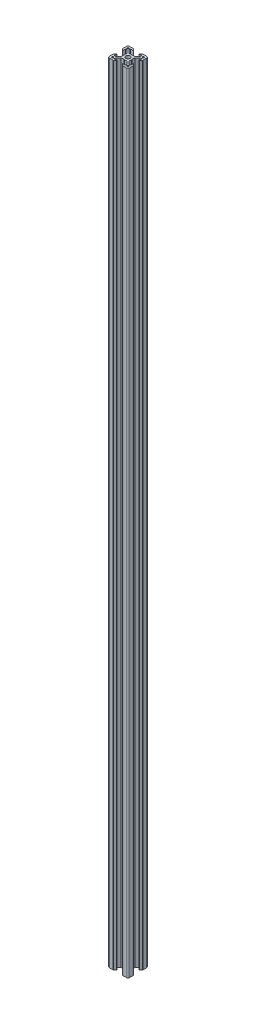
SolidWorks part; units mm, degrees
ref_plane "Front Plane" through (0, 0, 0) normal (0, 0, 1) x (1, 0, 0)
ref_plane "Top Plane" through (0, 0, 0) normal (0, 1, 0) x (1, 0, 0)
ref_plane "Right Plane" through (0, 0, 0) normal (1, 0, 0) x (0, 0, -1)
ref_plane "Plane1" through (0, 680, 0) normal (0, 1, 0) x (1, 0, 0)
sketch "Sketch1" plane through (0, 680, 0) normal (0, 1, 0) x (1, 0, 0)
  line L0 (16.2467, -17.2837) -> (16.2467, -18.911)
  line L1 (16.2467, -18.911) -> (14.6194, -18.911)
  line L2 (14.6194, -18.911) -> (14.6194, -18.3685)
  line L3 (14.6194, -18.3685) -> (15.7042, -17.2837)
  line L4 (15.7042, -17.2837) -> (16.2467, -17.2837)
  line L5 (16.2467, -4.1382) -> (15.7042, -4.1382)
  line L6 (15.7042, -4.1382) -> (14.6194, -3.0534)
  line L7 (14.6194, -3.0534) -> (14.6194, -2.511)
  line L8 (14.6194, -2.511) -> (16.2467, -2.511)
  line L9 (16.2467, -2.511) -> (16.2467, -4.1382)
  line L10 (-0.1533, -18.911) -> (-0.1533, -17.2837)
  line L11 (-0.1533, -17.2837) -> (0.3891, -17.2837)
  line L12 (0.3891, -17.2837) -> (1.4739, -18.3685)
  line L13 (1.4739, -18.3685) -> (1.4739, -18.911)
  line L14 (1.4739, -18.911) -> (-0.1533, -18.911)
  line L15 (1.4739, -2.511) -> (1.4739, -3.0534)
  line L16 (1.4739, -3.0534) -> (0.3891, -4.1382)
  line L17 (0.3891, -4.1382) -> (-0.1533, -4.1382)
  line L18 (-0.1533, -4.1382) -> (-0.1533, -2.511)
  line L19 (-0.1533, -2.511) -> (1.4739, -2.511)
  line L20 (3.2152, -0.711) -> (-0.4533, -0.711)
  line L21 (-1.9533, -2.211) -> (-1.9533, -5.811)
  line L22 (-1.7755, -6.3088) -> (-0.26, -7.8243)
  line L23 (-0.26, -7.8243) -> (-0.1533, -7.8243)
  line L24 (-0.1533, -7.8243) -> (-0.1533, -5.211)
  line L25 (-0.1533, -5.211) -> (1.486, -5.211)
  line L26 (1.486, -5.211) -> (4.1467, -7.8716)
  line L27 (4.1467, -7.8716) -> (4.1467, -10.5111)
  line L28 (4.1467, -10.5111) -> (4.3465, -10.711)
  line L29 (4.3465, -10.711) -> (4.1467, -10.9108)
  line L30 (4.1467, -10.9108) -> (4.1467, -13.5503)
  line L31 (4.1467, -13.5503) -> (1.486, -16.211)
  line L32 (1.486, -16.211) -> (-0.1533, -16.211)
  line L33 (-0.1533, -16.211) -> (-0.1533, -13.5976)
  line L34 (-0.1533, -13.5976) -> (-0.26, -13.5976)
  line L35 (-0.26, -13.5976) -> (-1.7755, -15.1132)
  line L36 (-1.9533, -15.611) -> (-1.9533, -19.211)
  line L37 (-0.4533, -20.711) -> (3.2152, -20.711)
  line L38 (3.6445, -20.5332) -> (5.16, -19.0176)
  line L39 (5.16, -19.0176) -> (5.16, -18.911)
  line L40 (5.16, -18.911) -> (2.5467, -18.911)
  line L41 (2.5467, -18.911) -> (2.5467, -17.2716)
  line L42 (2.5467, -17.2716) -> (5.2073, -14.611)
  line L43 (5.2073, -14.611) -> (7.8397, -14.611)
  line L44 (7.8397, -14.611) -> (8.0467, -14.4062)
  line L45 (8.0467, -14.4062) -> (8.2514, -14.611)
  line L46 (8.2514, -14.611) -> (10.886, -14.611)
  line L47 (10.886, -14.611) -> (13.5467, -17.2716)
  line L48 (13.5467, -17.2716) -> (13.5467, -18.911)
  line L49 (13.5467, -18.911) -> (10.9333, -18.911)
  line L50 (10.9333, -18.911) -> (10.9333, -19.0176)
  line L51 (10.9333, -19.0176) -> (12.4489, -20.5332)
  line L52 (12.8781, -20.711) -> (16.5467, -20.711)
  line L53 (18.0467, -19.211) -> (18.0467, -15.5424)
  line L54 (17.8689, -15.1132) -> (16.3533, -13.5976)
  line L55 (16.3533, -13.5976) -> (16.2467, -13.5976)
  line L56 (16.2467, -13.5976) -> (16.2467, -16.211)
  line L57 (16.2467, -16.211) -> (14.6073, -16.211)
  line L58 (14.6073, -16.211) -> (11.9467, -13.5503)
  line L59 (11.9467, -13.5503) -> (11.9467, -10.9108)
  line L60 (11.9467, -10.9108) -> (11.7468, -10.711)
  line L61 (11.7468, -10.711) -> (11.9467, -10.5111)
  line L62 (11.9467, -10.5111) -> (11.9467, -7.8716)
  line L63 (11.9467, -7.8716) -> (14.6073, -5.211)
  line L64 (14.6073, -5.211) -> (16.2467, -5.211)
  line L65 (16.2467, -5.211) -> (16.2467, -7.8243)
  line L66 (16.2467, -7.8243) -> (16.3533, -7.8243)
  line L67 (16.3533, -7.8243) -> (17.8689, -6.3088)
  line L68 (18.0467, -5.8795) -> (18.0467, -2.211)
  line L69 (16.5467, -0.711) -> (12.8781, -0.711)
  line L70 (12.4489, -0.8888) -> (10.9333, -2.4043)
  line L71 (10.9333, -2.4043) -> (10.9333, -2.511)
  line L72 (10.9333, -2.511) -> (13.5467, -2.511)
  line L73 (13.5467, -2.511) -> (13.5467, -4.1503)
  line L74 (13.5467, -4.1503) -> (10.886, -6.811)
  line L75 (10.886, -6.811) -> (8.2514, -6.811)
  line L76 (8.2514, -6.811) -> (8.0467, -7.0157)
  line L77 (8.0467, -7.0157) -> (7.8419, -6.811)
  line L78 (7.8419, -6.811) -> (5.2073, -6.811)
  line L79 (5.2073, -6.811) -> (2.5467, -4.1503)
  line L80 (2.5467, -4.1503) -> (2.5467, -2.511)
  line L81 (2.5467, -2.511) -> (5.16, -2.511)
  line L82 (5.16, -2.511) -> (5.16, -2.4043)
  line L83 (5.16, -2.4043) -> (3.6445, -0.8888)
  circle A0 centre (8.0467, -10.711) radius 2.1
  arc A1 (-0.4533, -0.711) -> (-1.9533, -2.211) centre (-0.4533, -2.211) ccw
  arc A2 (-1.9533, -5.811) -> (-1.7755, -6.3088) centre (-1.3389, -5.8722) ccw
  arc A3 (-1.7755, -15.1132) -> (-1.9533, -15.611) centre (-1.1676, -15.611) ccw
  arc A4 (-1.9533, -19.211) -> (-0.4533, -20.711) centre (-0.4533, -19.211) ccw
  arc A5 (3.2152, -20.711) -> (3.6445, -20.5332) centre (3.2152, -20.1039) ccw
  arc A6 (12.4489, -20.5332) -> (12.8781, -20.711) centre (12.8781, -20.1039) ccw
  arc A7 (16.5467, -20.711) -> (18.0467, -19.211) centre (16.5467, -19.211) ccw
  arc A8 (18.0467, -15.5424) -> (17.8689, -15.1132) centre (17.4396, -15.5424) ccw
  arc A9 (17.8689, -6.3088) -> (18.0467, -5.8795) centre (17.4396, -5.8795) ccw
  arc A10 (18.0467, -2.211) -> (16.5467, -0.711) centre (16.5467, -2.211) ccw
  arc A11 (12.8781, -0.711) -> (12.4489, -0.8888) centre (12.8781, -1.318) ccw
  arc A12 (3.6445, -0.8888) -> (3.2152, -0.711) centre (3.2152, -1.318) ccw
sketch "Sketch2" plane through (0, 680, 0) normal (0, 1, 0) x (1, 0, 0)
  line L5 (15.7042, -4.1382) -> (16.2467, -4.1382)
  line L6 (14.6194, -3.0534) -> (15.7042, -4.1382)
  line L7 (14.6194, -2.511) -> (14.6194, -3.0534)
  line L8 (16.2467, -2.511) -> (14.6194, -2.511)
  line L9 (16.2467, -4.1382) -> (16.2467, -2.511)
  line L10 (15.7042, -4.1382) -> (16.2467, -4.1382)
  line L11 (14.6194, -3.0534) -> (15.7042, -4.1382)
  line L12 (14.6194, -2.511) -> (14.6194, -3.0534)
  line L13 (16.2467, -2.511) -> (14.6194, -2.511)
  line L14 (16.2467, -4.1382) -> (16.2467, -2.511)
  line L15 (16.2467, -18.911) -> (16.2467, -17.2837)
  line L16 (14.6194, -18.911) -> (16.2467, -18.911)
  line L17 (14.6194, -18.3685) -> (14.6194, -18.911)
  line L18 (15.7042, -17.2837) -> (14.6194, -18.3685)
  line L19 (16.2467, -17.2837) -> (15.7042, -17.2837)
  line L20 (16.2467, -18.911) -> (16.2467, -17.2837)
  line L21 (14.6194, -18.911) -> (16.2467, -18.911)
  line L22 (14.6194, -18.3685) -> (14.6194, -18.911)
  line L23 (15.7042, -17.2837) -> (14.6194, -18.3685)
  line L24 (16.2467, -17.2837) -> (15.7042, -17.2837)
  line L25 (1.4739, -3.0534) -> (1.4739, -2.511)
  line L26 (0.3891, -4.1382) -> (1.4739, -3.0534)
  line L27 (-0.1533, -4.1382) -> (0.3891, -4.1382)
  line L28 (-0.1533, -2.511) -> (-0.1533, -4.1382)
  line L29 (1.4739, -2.511) -> (-0.1533, -2.511)
  line L30 (1.4739, -3.0534) -> (1.4739, -2.511)
  line L31 (0.3891, -4.1382) -> (1.4739, -3.0534)
  line L32 (-0.1533, -4.1382) -> (0.3891, -4.1382)
  line L33 (-0.1533, -2.511) -> (-0.1533, -4.1382)
  line L34 (1.4739, -2.511) -> (-0.1533, -2.511)
  line L35 (1.4739, -18.911) -> (1.4739, -18.3685)
  line L36 (1.4739, -18.3685) -> (0.3891, -17.2837)
  line L37 (0.3891, -17.2837) -> (-0.1533, -17.2837)
  line L38 (-0.1533, -17.2837) -> (-0.1533, -18.911)
  line L39 (-0.1533, -18.911) -> (1.4739, -18.911)
  line L40 (1.4739, -18.911) -> (1.4739, -18.3685)
  line L41 (1.4739, -18.3685) -> (0.3891, -17.2837)
  line L42 (0.3891, -17.2837) -> (-0.1533, -17.2837)
  line L43 (-0.1533, -17.2837) -> (-0.1533, -18.911)
  line L44 (-0.1533, -18.911) -> (1.4739, -18.911)
  line L104 (10.9333, -2.511) -> (13.5467, -2.511)
  line L105 (13.5467, -2.511) -> (13.5467, -4.1503)
  line L106 (13.5467, -4.1503) -> (10.886, -6.811)
  line L107 (10.886, -6.811) -> (8.2514, -6.811)
  line L108 (8.2514, -6.811) -> (8.0467, -7.0157)
  line L109 (8.0467, -7.0157) -> (7.8419, -6.811)
  line L110 (7.8419, -6.811) -> (5.2073, -6.811)
  line L111 (5.2073, -6.811) -> (2.5467, -4.1503)
  line L112 (2.5467, -4.1503) -> (2.5467, -2.511)
  line L113 (2.5467, -2.511) -> (5.16, -2.511)
  line L114 (5.16, -2.511) -> (5.16, -2.4043)
  line L115 (5.16, -2.4043) -> (3.6445, -0.8888)
  line L116 (3.2152, -0.711) -> (-0.4533, -0.711)
  line L117 (-1.9533, -2.211) -> (-1.9533, -5.811)
  line L118 (-1.7755, -6.3088) -> (-0.26, -7.8243)
  line L119 (-0.26, -7.8243) -> (-0.1533, -7.8243)
  line L120 (-0.1533, -7.8243) -> (-0.1533, -5.211)
  line L121 (-0.1533, -5.211) -> (1.486, -5.211)
  line L122 (1.486, -5.211) -> (4.1467, -7.8716)
  line L123 (4.1467, -7.8716) -> (4.1467, -10.5111)
  line L124 (4.1467, -10.5111) -> (4.3465, -10.711)
  line L125 (4.3465, -10.711) -> (4.1467, -10.9108)
  line L126 (4.1467, -10.9108) -> (4.1467, -13.5503)
  line L127 (4.1467, -13.5503) -> (1.486, -16.211)
  line L128 (1.486, -16.211) -> (-0.1533, -16.211)
  line L129 (-0.1533, -16.211) -> (-0.1533, -13.5976)
  line L130 (-0.1533, -13.5976) -> (-0.26, -13.5976)
  line L131 (-0.26, -13.5976) -> (-1.7755, -15.1132)
  line L132 (-1.9533, -15.611) -> (-1.9533, -19.211)
  line L133 (-0.4533, -20.711) -> (3.2152, -20.711)
  line L134 (3.6445, -20.5332) -> (5.16, -19.0176)
  line L135 (5.16, -19.0176) -> (5.16, -18.911)
  line L136 (5.16, -18.911) -> (2.5467, -18.911)
  line L137 (2.5467, -18.911) -> (2.5467, -17.2716)
  line L138 (2.5467, -17.2716) -> (5.2073, -14.611)
  line L139 (5.2073, -14.611) -> (7.8397, -14.611)
  line L140 (7.8397, -14.611) -> (8.0467, -14.4062)
  line L141 (8.0467, -14.4062) -> (8.2514, -14.611)
  line L142 (8.2514, -14.611) -> (10.886, -14.611)
  line L143 (10.886, -14.611) -> (13.5467, -17.2716)
  line L144 (13.5467, -17.2716) -> (13.5467, -18.911)
  line L145 (13.5467, -18.911) -> (10.9333, -18.911)
  line L146 (10.9333, -18.911) -> (10.9333, -19.0176)
  line L147 (10.9333, -19.0176) -> (12.4489, -20.5332)
  line L148 (12.8781, -20.711) -> (16.5467, -20.711)
  line L149 (18.0467, -19.211) -> (18.0467, -15.5424)
  line L150 (17.8689, -15.1132) -> (16.3533, -13.5976)
  line L151 (16.3533, -13.5976) -> (16.2467, -13.5976)
  line L152 (16.2467, -13.5976) -> (16.2467, -16.211)
  line L153 (16.2467, -16.211) -> (14.6073, -16.211)
  line L154 (14.6073, -16.211) -> (11.9467, -13.5503)
  line L155 (11.9467, -13.5503) -> (11.9467, -10.9108)
  line L156 (11.9467, -10.9108) -> (11.7468, -10.711)
  line L157 (11.7468, -10.711) -> (11.9467, -10.5111)
  line L158 (11.9467, -10.5111) -> (11.9467, -7.8716)
  line L159 (11.9467, -7.8716) -> (14.6073, -5.211)
  line L160 (14.6073, -5.211) -> (16.2467, -5.211)
  line L161 (16.2467, -5.211) -> (16.2467, -7.8243)
  line L162 (16.2467, -7.8243) -> (16.3533, -7.8243)
  line L163 (16.3533, -7.8243) -> (17.8689, -6.3088)
  line L164 (18.0467, -5.8795) -> (18.0467, -2.211)
  line L165 (16.5467, -0.711) -> (12.8781, -0.711)
  line L166 (12.4489, -0.8888) -> (10.9333, -2.4043)
  line L167 (10.9333, -2.4043) -> (10.9333, -2.511)
  line L168 (10.9333, -2.511) -> (13.5467, -2.511)
  line L169 (13.5467, -2.511) -> (13.5467, -4.1503)
  line L170 (13.5467, -4.1503) -> (10.886, -6.811)
  line L171 (10.886, -6.811) -> (8.2514, -6.811)
  line L172 (8.2514, -6.811) -> (8.0467, -7.0157)
  line L173 (8.0467, -7.0157) -> (7.8419, -6.811)
  line L174 (7.8419, -6.811) -> (5.2073, -6.811)
  line L175 (5.2073, -6.811) -> (2.5467, -4.1503)
  line L176 (2.5467, -4.1503) -> (2.5467, -2.511)
  line L177 (2.5467, -2.511) -> (5.16, -2.511)
  line L178 (5.16, -2.511) -> (5.16, -2.4043)
  line L179 (5.16, -2.4043) -> (3.6445, -0.8888)
  line L180 (3.2152, -0.711) -> (-0.4533, -0.711)
  line L181 (-1.9533, -2.211) -> (-1.9533, -5.811)
  line L182 (-1.7755, -6.3088) -> (-0.26, -7.8243)
  line L183 (-0.26, -7.8243) -> (-0.1533, -7.8243)
  line L184 (-0.1533, -7.8243) -> (-0.1533, -5.211)
  line L185 (-0.1533, -5.211) -> (1.486, -5.211)
  line L186 (1.486, -5.211) -> (4.1467, -7.8716)
  line L187 (4.1467, -7.8716) -> (4.1467, -10.5111)
  line L188 (4.1467, -10.5111) -> (4.3465, -10.711)
  line L189 (4.3465, -10.711) -> (4.1467, -10.9108)
  line L190 (4.1467, -10.9108) -> (4.1467, -13.5503)
  line L191 (4.1467, -13.5503) -> (1.486, -16.211)
  line L192 (1.486, -16.211) -> (-0.1533, -16.211)
  line L193 (-0.1533, -16.211) -> (-0.1533, -13.5976)
  line L194 (-0.1533, -13.5976) -> (-0.26, -13.5976)
  line L195 (-0.26, -13.5976) -> (-1.7755, -15.1132)
  line L196 (-1.9533, -15.611) -> (-1.9533, -19.211)
  line L197 (-0.4533, -20.711) -> (3.2152, -20.711)
  line L198 (3.6445, -20.5332) -> (5.16, -19.0176)
  line L199 (5.16, -19.0176) -> (5.16, -18.911)
  line L200 (5.16, -18.911) -> (2.5467, -18.911)
  line L201 (2.5467, -18.911) -> (2.5467, -17.2716)
  line L202 (2.5467, -17.2716) -> (5.2073, -14.611)
  line L203 (5.2073, -14.611) -> (7.8397, -14.611)
  line L204 (7.8397, -14.611) -> (8.0467, -14.4062)
  line L205 (8.0467, -14.4062) -> (8.2514, -14.611)
  line L206 (8.2514, -14.611) -> (10.886, -14.611)
  line L207 (10.886, -14.611) -> (13.5467, -17.2716)
  line L208 (13.5467, -17.2716) -> (13.5467, -18.911)
  line L209 (13.5467, -18.911) -> (10.9333, -18.911)
  line L210 (10.9333, -18.911) -> (10.9333, -19.0176)
  line L211 (10.9333, -19.0176) -> (12.4489, -20.5332)
  line L212 (12.8781, -20.711) -> (16.5467, -20.711)
  line L213 (18.0467, -19.211) -> (18.0467, -15.5424)
  line L214 (17.8689, -15.1132) -> (16.3533, -13.5976)
  line L215 (16.3533, -13.5976) -> (16.2467, -13.5976)
  line L216 (16.2467, -13.5976) -> (16.2467, -16.211)
  line L217 (16.2467, -16.211) -> (14.6073, -16.211)
  line L218 (14.6073, -16.211) -> (11.9467, -13.5503)
  line L219 (11.9467, -13.5503) -> (11.9467, -10.9108)
  line L220 (11.9467, -10.9108) -> (11.7468, -10.711)
  line L221 (11.7468, -10.711) -> (11.9467, -10.5111)
  line L222 (11.9467, -10.5111) -> (11.9467, -7.8716)
  line L223 (11.9467, -7.8716) -> (14.6073, -5.211)
  line L224 (14.6073, -5.211) -> (16.2467, -5.211)
  line L225 (16.2467, -5.211) -> (16.2467, -7.8243)
  line L226 (16.2467, -7.8243) -> (16.3533, -7.8243)
  line L227 (16.3533, -7.8243) -> (17.8689, -6.3088)
  line L228 (18.0467, -5.8795) -> (18.0467, -2.211)
  line L229 (16.5467, -0.711) -> (12.8781, -0.711)
  line L230 (12.4489, -0.8888) -> (10.9333, -2.4043)
  line L231 (10.9333, -2.4043) -> (10.9333, -2.511)
  circle A1 centre (8.0467, -10.711) radius 2.1
  circle A2 centre (8.0467, -10.711) radius 2.1
  arc A14 (3.6445, -0.8888) -> (3.2152, -0.711) centre (3.2152, -1.318) ccw
  arc A15 (-0.4533, -0.711) -> (-1.9533, -2.211) centre (-0.4533, -2.211) ccw
  arc A16 (-1.9533, -5.811) -> (-1.7755, -6.3088) centre (-1.3389, -5.8722) ccw
  arc A17 (-1.7755, -15.1132) -> (-1.9533, -15.611) centre (-1.1676, -15.611) ccw
  arc A18 (-1.9533, -19.211) -> (-0.4533, -20.711) centre (-0.4533, -19.211) ccw
  arc A19 (3.2152, -20.711) -> (3.6445, -20.5332) centre (3.2152, -20.1039) ccw
  arc A20 (12.4489, -20.5332) -> (12.8781, -20.711) centre (12.8781, -20.1039) ccw
  arc A21 (16.5467, -20.711) -> (18.0467, -19.211) centre (16.5467, -19.211) ccw
  arc A22 (18.0467, -15.5424) -> (17.8689, -15.1132) centre (17.4396, -15.5424) ccw
  arc A23 (17.8689, -6.3088) -> (18.0467, -5.8795) centre (17.4396, -5.8795) ccw
  arc A24 (18.0467, -2.211) -> (16.5467, -0.711) centre (16.5467, -2.211) ccw
  arc A25 (12.8781, -0.711) -> (12.4489, -0.8888) centre (12.8781, -1.318) ccw
  arc A26 (3.6445, -0.8888) -> (3.2152, -0.711) centre (3.2152, -1.318) ccw
  arc A27 (-0.4533, -0.711) -> (-1.9533, -2.211) centre (-0.4533, -2.211) ccw
  arc A28 (-1.9533, -5.811) -> (-1.7755, -6.3088) centre (-1.3389, -5.8722) ccw
  arc A29 (-1.7755, -15.1132) -> (-1.9533, -15.611) centre (-1.1676, -15.611) ccw
  arc A30 (-1.9533, -19.211) -> (-0.4533, -20.711) centre (-0.4533, -19.211) ccw
  arc A31 (3.2152, -20.711) -> (3.6445, -20.5332) centre (3.2152, -20.1039) ccw
  arc A32 (12.4489, -20.5332) -> (12.8781, -20.711) centre (12.8781, -20.1039) ccw
  arc A33 (16.5467, -20.711) -> (18.0467, -19.211) centre (16.5467, -19.211) ccw
  arc A34 (18.0467, -15.5424) -> (17.8689, -15.1132) centre (17.4396, -15.5424) ccw
  arc A35 (17.8689, -6.3088) -> (18.0467, -5.8795) centre (17.4396, -5.8795) ccw
  arc A36 (18.0467, -2.211) -> (16.5467, -0.711) centre (16.5467, -2.211) ccw
  arc A37 (12.8781, -0.711) -> (12.4489, -0.8888) centre (12.8781, -1.318) ccw
  dimension "D1" = 0
  dimension "D2" = 0
  dimension "D3" = 0
  dimension "D4" = 0
  dimension "D5" = 0
  dimension "D6" = 0
extrude "Boss-Extrude2" [suppressed] add sketch "Sketch2" against normal blind 680
sketch "Sketch3" [suppressed] plane through (0, 680, 0) normal (0, 1, 0) x (1, 0, 0)
  line L5 (15.7042, -4.1382) -> (16.2467, -4.1382)
  line L6 (14.6194, -3.0534) -> (15.7042, -4.1382)
  line L7 (14.6194, -2.511) -> (14.6194, -3.0534)
  line L8 (16.2467, -2.511) -> (14.6194, -2.511)
  line L9 (16.2467, -4.1382) -> (16.2467, -2.511)
  line L10 (15.7042, -4.1382) -> (16.2467, -4.1382)
  line L11 (14.6194, -3.0534) -> (15.7042, -4.1382)
  line L12 (14.6194, -2.511) -> (14.6194, -3.0534)
  line L13 (16.2467, -2.511) -> (14.6194, -2.511)
  line L14 (16.2467, -4.1382) -> (16.2467, -2.511)
  line L15 (16.2467, -18.911) -> (16.2467, -17.2837)
  line L16 (14.6194, -18.911) -> (16.2467, -18.911)
  line L17 (14.6194, -18.3685) -> (14.6194, -18.911)
  line L18 (15.7042, -17.2837) -> (14.6194, -18.3685)
  line L19 (16.2467, -17.2837) -> (15.7042, -17.2837)
  line L20 (16.2467, -18.911) -> (16.2467, -17.2837)
  line L21 (14.6194, -18.911) -> (16.2467, -18.911)
  line L22 (14.6194, -18.3685) -> (14.6194, -18.911)
  line L23 (15.7042, -17.2837) -> (14.6194, -18.3685)
  line L24 (16.2467, -17.2837) -> (15.7042, -17.2837)
  line L25 (1.4739, -3.0534) -> (1.4739, -2.511)
  line L26 (0.3891, -4.1382) -> (1.4739, -3.0534)
  line L27 (-0.1533, -4.1382) -> (0.3891, -4.1382)
  line L28 (-0.1533, -2.511) -> (-0.1533, -4.1382)
  line L29 (1.4739, -2.511) -> (-0.1533, -2.511)
  line L30 (1.4739, -3.0534) -> (1.4739, -2.511)
  line L31 (0.3891, -4.1382) -> (1.4739, -3.0534)
  line L32 (-0.1533, -4.1382) -> (0.3891, -4.1382)
  line L33 (-0.1533, -2.511) -> (-0.1533, -4.1382)
  line L34 (1.4739, -2.511) -> (-0.1533, -2.511)
  line L35 (1.4739, -18.911) -> (1.4739, -18.3685)
  line L36 (1.4739, -18.3685) -> (0.3891, -17.2837)
  line L37 (0.3891, -17.2837) -> (-0.1533, -17.2837)
  line L38 (-0.1533, -17.2837) -> (-0.1533, -18.911)
  line L39 (-0.1533, -18.911) -> (1.4739, -18.911)
  line L40 (1.4739, -18.911) -> (1.4739, -18.3685)
  line L41 (1.4739, -18.3685) -> (0.3891, -17.2837)
  line L42 (0.3891, -17.2837) -> (-0.1533, -17.2837)
  line L43 (-0.1533, -17.2837) -> (-0.1533, -18.911)
  line L44 (-0.1533, -18.911) -> (1.4739, -18.911)
  line L104 (10.9333, -2.511) -> (13.5467, -2.511)
  line L105 (13.5467, -2.511) -> (13.5467, -4.1503)
  line L106 (13.5467, -4.1503) -> (10.886, -6.811)
  line L107 (10.886, -6.811) -> (8.2514, -6.811)
  line L108 (8.2514, -6.811) -> (8.0467, -7.0157)
  line L109 (8.0467, -7.0157) -> (7.8419, -6.811)
  line L110 (7.8419, -6.811) -> (5.2073, -6.811)
  line L111 (5.2073, -6.811) -> (2.5467, -4.1503)
  line L112 (2.5467, -4.1503) -> (2.5467, -2.511)
  line L113 (2.5467, -2.511) -> (5.16, -2.511)
  line L114 (5.16, -2.511) -> (5.16, -2.4043)
  line L115 (5.16, -2.4043) -> (3.6445, -0.8888)
  line L116 (3.2152, -0.711) -> (-0.4533, -0.711)
  line L117 (-1.9533, -2.211) -> (-1.9533, -5.811)
  line L118 (-1.7755, -6.3088) -> (-0.26, -7.8243)
  line L119 (-0.26, -7.8243) -> (-0.1533, -7.8243)
  line L120 (-0.1533, -7.8243) -> (-0.1533, -5.211)
  line L121 (-0.1533, -5.211) -> (1.486, -5.211)
  line L122 (1.486, -5.211) -> (4.1467, -7.8716)
  line L123 (4.1467, -7.8716) -> (4.1467, -10.5111)
  line L124 (4.1467, -10.5111) -> (4.3465, -10.711)
  line L125 (4.3465, -10.711) -> (4.1467, -10.9108)
  line L126 (4.1467, -10.9108) -> (4.1467, -13.5503)
  line L127 (4.1467, -13.5503) -> (1.486, -16.211)
  line L128 (1.486, -16.211) -> (-0.1533, -16.211)
  line L129 (-0.1533, -16.211) -> (-0.1533, -13.5976)
  line L130 (-0.1533, -13.5976) -> (-0.26, -13.5976)
  line L131 (-0.26, -13.5976) -> (-1.7755, -15.1132)
  line L132 (-1.9533, -15.611) -> (-1.9533, -19.211)
  line L133 (-0.4533, -20.711) -> (3.2152, -20.711)
  line L134 (3.6445, -20.5332) -> (5.16, -19.0176)
  line L135 (5.16, -19.0176) -> (5.16, -18.911)
  line L136 (5.16, -18.911) -> (2.5467, -18.911)
  line L137 (2.5467, -18.911) -> (2.5467, -17.2716)
  line L138 (2.5467, -17.2716) -> (5.2073, -14.611)
  line L139 (5.2073, -14.611) -> (7.8397, -14.611)
  line L140 (7.8397, -14.611) -> (8.0467, -14.4062)
  line L141 (8.0467, -14.4062) -> (8.2514, -14.611)
  line L142 (8.2514, -14.611) -> (10.886, -14.611)
  line L143 (10.886, -14.611) -> (13.5467, -17.2716)
  line L144 (13.5467, -17.2716) -> (13.5467, -18.911)
  line L145 (13.5467, -18.911) -> (10.9333, -18.911)
  line L146 (10.9333, -18.911) -> (10.9333, -19.0176)
  line L147 (10.9333, -19.0176) -> (12.4489, -20.5332)
  line L148 (12.8781, -20.711) -> (16.5467, -20.711)
  line L149 (18.0467, -19.211) -> (18.0467, -15.5424)
  line L150 (17.8689, -15.1132) -> (16.3533, -13.5976)
  line L151 (16.3533, -13.5976) -> (16.2467, -13.5976)
  line L152 (16.2467, -13.5976) -> (16.2467, -16.211)
  line L153 (16.2467, -16.211) -> (14.6073, -16.211)
  line L154 (14.6073, -16.211) -> (11.9467, -13.5503)
  line L155 (11.9467, -13.5503) -> (11.9467, -10.9108)
  line L156 (11.9467, -10.9108) -> (11.7468, -10.711)
  line L157 (11.7468, -10.711) -> (11.9467, -10.5111)
  line L158 (11.9467, -10.5111) -> (11.9467, -7.8716)
  line L159 (11.9467, -7.8716) -> (14.6073, -5.211)
  line L160 (14.6073, -5.211) -> (16.2467, -5.211)
  line L161 (16.2467, -5.211) -> (16.2467, -7.8243)
  line L162 (16.2467, -7.8243) -> (16.3533, -7.8243)
  line L163 (16.3533, -7.8243) -> (17.8689, -6.3088)
  line L164 (18.0467, -5.8795) -> (18.0467, -2.211)
  line L165 (16.5467, -0.711) -> (12.8781, -0.711)
  line L166 (12.4489, -0.8888) -> (10.9333, -2.4043)
  line L167 (10.9333, -2.4043) -> (10.9333, -2.511)
  line L168 (10.9333, -2.511) -> (13.5467, -2.511)
  line L169 (13.5467, -2.511) -> (13.5467, -4.1503)
  line L170 (13.5467, -4.1503) -> (10.886, -6.811)
  line L171 (10.886, -6.811) -> (8.2514, -6.811)
  line L172 (8.2514, -6.811) -> (8.0467, -7.0157)
  line L173 (8.0467, -7.0157) -> (7.8419, -6.811)
  line L174 (7.8419, -6.811) -> (5.2073, -6.811)
  line L175 (5.2073, -6.811) -> (2.5467, -4.1503)
  line L176 (2.5467, -4.1503) -> (2.5467, -2.511)
  line L177 (2.5467, -2.511) -> (5.16, -2.511)
  line L178 (5.16, -2.511) -> (5.16, -2.4043)
  line L179 (5.16, -2.4043) -> (3.6445, -0.8888)
  line L180 (3.2152, -0.711) -> (-0.4533, -0.711)
  line L181 (-1.9533, -2.211) -> (-1.9533, -5.811)
  line L182 (-1.7755, -6.3088) -> (-0.26, -7.8243)
  line L183 (-0.26, -7.8243) -> (-0.1533, -7.8243)
  line L184 (-0.1533, -7.8243) -> (-0.1533, -5.211)
  line L185 (-0.1533, -5.211) -> (1.486, -5.211)
  line L186 (1.486, -5.211) -> (4.1467, -7.8716)
  line L187 (4.1467, -7.8716) -> (4.1467, -10.5111)
  line L188 (4.1467, -10.5111) -> (4.3465, -10.711)
  line L189 (4.3465, -10.711) -> (4.1467, -10.9108)
  line L190 (4.1467, -10.9108) -> (4.1467, -13.5503)
  line L191 (4.1467, -13.5503) -> (1.486, -16.211)
  line L192 (1.486, -16.211) -> (-0.1533, -16.211)
  line L193 (-0.1533, -16.211) -> (-0.1533, -13.5976)
  line L194 (-0.1533, -13.5976) -> (-0.26, -13.5976)
  line L195 (-0.26, -13.5976) -> (-1.7755, -15.1132)
  line L196 (-1.9533, -15.611) -> (-1.9533, -19.211)
  line L197 (-0.4533, -20.711) -> (3.2152, -20.711)
  line L198 (3.6445, -20.5332) -> (5.16, -19.0176)
  line L199 (5.16, -19.0176) -> (5.16, -18.911)
  line L200 (5.16, -18.911) -> (2.5467, -18.911)
  line L201 (2.5467, -18.911) -> (2.5467, -17.2716)
  line L202 (2.5467, -17.2716) -> (5.2073, -14.611)
  line L203 (5.2073, -14.611) -> (7.8397, -14.611)
  line L204 (7.8397, -14.611) -> (8.0467, -14.4062)
  line L205 (8.0467, -14.4062) -> (8.2514, -14.611)
  line L206 (8.2514, -14.611) -> (10.886, -14.611)
  line L207 (10.886, -14.611) -> (13.5467, -17.2716)
  line L208 (13.5467, -17.2716) -> (13.5467, -18.911)
  line L209 (13.5467, -18.911) -> (10.9333, -18.911)
  line L210 (10.9333, -18.911) -> (10.9333, -19.0176)
  line L211 (10.9333, -19.0176) -> (12.4489, -20.5332)
  line L212 (12.8781, -20.711) -> (16.5467, -20.711)
  line L213 (18.0467, -19.211) -> (18.0467, -15.5424)
  line L214 (17.8689, -15.1132) -> (16.3533, -13.5976)
  line L215 (16.3533, -13.5976) -> (16.2467, -13.5976)
  line L216 (16.2467, -13.5976) -> (16.2467, -16.211)
  line L217 (16.2467, -16.211) -> (14.6073, -16.211)
  line L218 (14.6073, -16.211) -> (11.9467, -13.5503)
  line L219 (11.9467, -13.5503) -> (11.9467, -10.9108)
  line L220 (11.9467, -10.9108) -> (11.7468, -10.711)
  line L221 (11.7468, -10.711) -> (11.9467, -10.5111)
  line L222 (11.9467, -10.5111) -> (11.9467, -7.8716)
  line L223 (11.9467, -7.8716) -> (14.6073, -5.211)
  line L224 (14.6073, -5.211) -> (16.2467, -5.211)
  line L225 (16.2467, -5.211) -> (16.2467, -7.8243)
  line L226 (16.2467, -7.8243) -> (16.3533, -7.8243)
  line L227 (16.3533, -7.8243) -> (17.8689, -6.3088)
  line L228 (18.0467, -5.8795) -> (18.0467, -2.211)
  line L229 (16.5467, -0.711) -> (12.8781, -0.711)
  line L230 (12.4489, -0.8888) -> (10.9333, -2.4043)
  line L231 (10.9333, -2.4043) -> (10.9333, -2.511)
  circle A1 centre (8.0467, -10.711) radius 2.1
  circle A2 centre (8.0467, -10.711) radius 2.1
  arc A14 (3.6445, -0.8888) -> (3.2152, -0.711) centre (3.2152, -1.318) ccw
  arc A15 (-0.4533, -0.711) -> (-1.9533, -2.211) centre (-0.4533, -2.211) ccw
  arc A16 (-1.9533, -5.811) -> (-1.7755, -6.3088) centre (-1.3389, -5.8722) ccw
  arc A17 (-1.7755, -15.1132) -> (-1.9533, -15.611) centre (-1.1676, -15.611) ccw
  arc A18 (-1.9533, -19.211) -> (-0.4533, -20.711) centre (-0.4533, -19.211) ccw
  arc A19 (3.2152, -20.711) -> (3.6445, -20.5332) centre (3.2152, -20.1039) ccw
  arc A20 (12.4489, -20.5332) -> (12.8781, -20.711) centre (12.8781, -20.1039) ccw
  arc A21 (16.5467, -20.711) -> (18.0467, -19.211) centre (16.5467, -19.211) ccw
  arc A22 (18.0467, -15.5424) -> (17.8689, -15.1132) centre (17.4396, -15.5424) ccw
  arc A23 (17.8689, -6.3088) -> (18.0467, -5.8795) centre (17.4396, -5.8795) ccw
  arc A24 (18.0467, -2.211) -> (16.5467, -0.711) centre (16.5467, -2.211) ccw
  arc A25 (12.8781, -0.711) -> (12.4489, -0.8888) centre (12.8781, -1.318) ccw
  arc A26 (3.6445, -0.8888) -> (3.2152, -0.711) centre (3.2152, -1.318) ccw
  arc A27 (-0.4533, -0.711) -> (-1.9533, -2.211) centre (-0.4533, -2.211) ccw
  arc A28 (-1.9533, -5.811) -> (-1.7755, -6.3088) centre (-1.3389, -5.8722) ccw
  arc A29 (-1.7755, -15.1132) -> (-1.9533, -15.611) centre (-1.1676, -15.611) ccw
  arc A30 (-1.9533, -19.211) -> (-0.4533, -20.711) centre (-0.4533, -19.211) ccw
  arc A31 (3.2152, -20.711) -> (3.6445, -20.5332) centre (3.2152, -20.1039) ccw
  arc A32 (12.4489, -20.5332) -> (12.8781, -20.711) centre (12.8781, -20.1039) ccw
  arc A33 (16.5467, -20.711) -> (18.0467, -19.211) centre (16.5467, -19.211) ccw
  arc A34 (18.0467, -15.5424) -> (17.8689, -15.1132) centre (17.4396, -15.5424) ccw
  arc A35 (17.8689, -6.3088) -> (18.0467, -5.8795) centre (17.4396, -5.8795) ccw
  arc A36 (18.0467, -2.211) -> (16.5467, -0.711) centre (16.5467, -2.211) ccw
  arc A37 (12.8781, -0.711) -> (12.4489, -0.8888) centre (12.8781, -1.318) ccw
  dimension "D1" = 0
  dimension "D2" = 0
  dimension "D3" = 0
  dimension "D4" = 0
  dimension "D5" = 0
  dimension "D6" = 0
extrude "Boss-Extrude3" [suppressed] add sketch "Sketch3" against normal blind 530
sketch "Sketch5" plane through (0, 680, 0) normal (0, 1, 0) x (1, 0, 0)
  line L5 (15.7042, -4.1382) -> (16.2467, -4.1382)
  line L6 (14.6194, -3.0534) -> (15.7042, -4.1382)
  line L7 (14.6194, -2.511) -> (14.6194, -3.0534)
  line L8 (16.2467, -2.511) -> (14.6194, -2.511)
  line L9 (16.2467, -4.1382) -> (16.2467, -2.511)
  line L10 (15.7042, -4.1382) -> (16.2467, -4.1382)
  line L11 (14.6194, -3.0534) -> (15.7042, -4.1382)
  line L12 (14.6194, -2.511) -> (14.6194, -3.0534)
  line L13 (16.2467, -2.511) -> (14.6194, -2.511)
  line L14 (16.2467, -4.1382) -> (16.2467, -2.511)
  line L15 (16.2467, -18.911) -> (16.2467, -17.2837)
  line L16 (14.6194, -18.911) -> (16.2467, -18.911)
  line L17 (14.6194, -18.3685) -> (14.6194, -18.911)
  line L18 (15.7042, -17.2837) -> (14.6194, -18.3685)
  line L19 (16.2467, -17.2837) -> (15.7042, -17.2837)
  line L20 (16.2467, -18.911) -> (16.2467, -17.2837)
  line L21 (14.6194, -18.911) -> (16.2467, -18.911)
  line L22 (14.6194, -18.3685) -> (14.6194, -18.911)
  line L23 (15.7042, -17.2837) -> (14.6194, -18.3685)
  line L24 (16.2467, -17.2837) -> (15.7042, -17.2837)
  line L25 (1.4739, -3.0534) -> (1.4739, -2.511)
  line L26 (0.3891, -4.1382) -> (1.4739, -3.0534)
  line L27 (-0.1533, -4.1382) -> (0.3891, -4.1382)
  line L28 (-0.1533, -2.511) -> (-0.1533, -4.1382)
  line L29 (1.4739, -2.511) -> (-0.1533, -2.511)
  line L30 (1.4739, -3.0534) -> (1.4739, -2.511)
  line L31 (0.3891, -4.1382) -> (1.4739, -3.0534)
  line L32 (-0.1533, -4.1382) -> (0.3891, -4.1382)
  line L33 (-0.1533, -2.511) -> (-0.1533, -4.1382)
  line L34 (1.4739, -2.511) -> (-0.1533, -2.511)
  line L35 (1.4739, -18.911) -> (1.4739, -18.3685)
  line L36 (1.4739, -18.3685) -> (0.3891, -17.2837)
  line L37 (0.3891, -17.2837) -> (-0.1533, -17.2837)
  line L38 (-0.1533, -17.2837) -> (-0.1533, -18.911)
  line L39 (-0.1533, -18.911) -> (1.4739, -18.911)
  line L40 (1.4739, -18.911) -> (1.4739, -18.3685)
  line L41 (1.4739, -18.3685) -> (0.3891, -17.2837)
  line L42 (0.3891, -17.2837) -> (-0.1533, -17.2837)
  line L43 (-0.1533, -17.2837) -> (-0.1533, -18.911)
  line L44 (-0.1533, -18.911) -> (1.4739, -18.911)
  line L104 (10.9333, -2.511) -> (13.5467, -2.511)
  line L105 (13.5467, -2.511) -> (13.5467, -4.1503)
  line L106 (13.5467, -4.1503) -> (10.886, -6.811)
  line L107 (10.886, -6.811) -> (8.2514, -6.811)
  line L108 (8.2514, -6.811) -> (8.0467, -7.0157)
  line L109 (8.0467, -7.0157) -> (7.8419, -6.811)
  line L110 (7.8419, -6.811) -> (5.2073, -6.811)
  line L111 (5.2073, -6.811) -> (2.5467, -4.1503)
  line L112 (2.5467, -4.1503) -> (2.5467, -2.511)
  line L113 (2.5467, -2.511) -> (5.16, -2.511)
  line L114 (5.16, -2.511) -> (5.16, -2.4043)
  line L115 (5.16, -2.4043) -> (3.6445, -0.8888)
  line L116 (3.2152, -0.711) -> (-0.4533, -0.711)
  line L117 (-1.9533, -2.211) -> (-1.9533, -5.811)
  line L118 (-1.7755, -6.3088) -> (-0.26, -7.8243)
  line L119 (-0.26, -7.8243) -> (-0.1533, -7.8243)
  line L120 (-0.1533, -7.8243) -> (-0.1533, -5.211)
  line L121 (-0.1533, -5.211) -> (1.486, -5.211)
  line L122 (1.486, -5.211) -> (4.1467, -7.8716)
  line L123 (4.1467, -7.8716) -> (4.1467, -10.5111)
  line L124 (4.1467, -10.5111) -> (4.3465, -10.711)
  line L125 (4.3465, -10.711) -> (4.1467, -10.9108)
  line L126 (4.1467, -10.9108) -> (4.1467, -13.5503)
  line L127 (4.1467, -13.5503) -> (1.486, -16.211)
  line L128 (1.486, -16.211) -> (-0.1533, -16.211)
  line L129 (-0.1533, -16.211) -> (-0.1533, -13.5976)
  line L130 (-0.1533, -13.5976) -> (-0.26, -13.5976)
  line L131 (-0.26, -13.5976) -> (-1.7755, -15.1132)
  line L132 (-1.9533, -15.611) -> (-1.9533, -19.211)
  line L133 (-0.4533, -20.711) -> (3.2152, -20.711)
  line L134 (3.6445, -20.5332) -> (5.16, -19.0176)
  line L135 (5.16, -19.0176) -> (5.16, -18.911)
  line L136 (5.16, -18.911) -> (2.5467, -18.911)
  line L137 (2.5467, -18.911) -> (2.5467, -17.2716)
  line L138 (2.5467, -17.2716) -> (5.2073, -14.611)
  line L139 (5.2073, -14.611) -> (7.8397, -14.611)
  line L140 (7.8397, -14.611) -> (8.0467, -14.4062)
  line L141 (8.0467, -14.4062) -> (8.2514, -14.611)
  line L142 (8.2514, -14.611) -> (10.886, -14.611)
  line L143 (10.886, -14.611) -> (13.5467, -17.2716)
  line L144 (13.5467, -17.2716) -> (13.5467, -18.911)
  line L145 (13.5467, -18.911) -> (10.9333, -18.911)
  line L146 (10.9333, -18.911) -> (10.9333, -19.0176)
  line L147 (10.9333, -19.0176) -> (12.4489, -20.5332)
  line L148 (12.8781, -20.711) -> (16.5467, -20.711)
  line L149 (18.0467, -19.211) -> (18.0467, -15.5424)
  line L150 (17.8689, -15.1132) -> (16.3533, -13.5976)
  line L151 (16.3533, -13.5976) -> (16.2467, -13.5976)
  line L152 (16.2467, -13.5976) -> (16.2467, -16.211)
  line L153 (16.2467, -16.211) -> (14.6073, -16.211)
  line L154 (14.6073, -16.211) -> (11.9467, -13.5503)
  line L155 (11.9467, -13.5503) -> (11.9467, -10.9108)
  line L156 (11.9467, -10.9108) -> (11.7468, -10.711)
  line L157 (11.7468, -10.711) -> (11.9467, -10.5111)
  line L158 (11.9467, -10.5111) -> (11.9467, -7.8716)
  line L159 (11.9467, -7.8716) -> (14.6073, -5.211)
  line L160 (14.6073, -5.211) -> (16.2467, -5.211)
  line L161 (16.2467, -5.211) -> (16.2467, -7.8243)
  line L162 (16.2467, -7.8243) -> (16.3533, -7.8243)
  line L163 (16.3533, -7.8243) -> (17.8689, -6.3088)
  line L164 (18.0467, -5.8795) -> (18.0467, -2.211)
  line L165 (16.5467, -0.711) -> (12.8781, -0.711)
  line L166 (12.4489, -0.8888) -> (10.9333, -2.4043)
  line L167 (10.9333, -2.4043) -> (10.9333, -2.511)
  line L168 (10.9333, -2.511) -> (13.5467, -2.511)
  line L169 (13.5467, -2.511) -> (13.5467, -4.1503)
  line L170 (13.5467, -4.1503) -> (10.886, -6.811)
  line L171 (10.886, -6.811) -> (8.2514, -6.811)
  line L172 (8.2514, -6.811) -> (8.0467, -7.0157)
  line L173 (8.0467, -7.0157) -> (7.8419, -6.811)
  line L174 (7.8419, -6.811) -> (5.2073, -6.811)
  line L175 (5.2073, -6.811) -> (2.5467, -4.1503)
  line L176 (2.5467, -4.1503) -> (2.5467, -2.511)
  line L177 (2.5467, -2.511) -> (5.16, -2.511)
  line L178 (5.16, -2.511) -> (5.16, -2.4043)
  line L179 (5.16, -2.4043) -> (3.6445, -0.8888)
  line L180 (3.2152, -0.711) -> (-0.4533, -0.711)
  line L181 (-1.9533, -2.211) -> (-1.9533, -5.811)
  line L182 (-1.7755, -6.3088) -> (-0.26, -7.8243)
  line L183 (-0.26, -7.8243) -> (-0.1533, -7.8243)
  line L184 (-0.1533, -7.8243) -> (-0.1533, -5.211)
  line L185 (-0.1533, -5.211) -> (1.486, -5.211)
  line L186 (1.486, -5.211) -> (4.1467, -7.8716)
  line L187 (4.1467, -7.8716) -> (4.1467, -10.5111)
  line L188 (4.1467, -10.5111) -> (4.3465, -10.711)
  line L189 (4.3465, -10.711) -> (4.1467, -10.9108)
  line L190 (4.1467, -10.9108) -> (4.1467, -13.5503)
  line L191 (4.1467, -13.5503) -> (1.486, -16.211)
  line L192 (1.486, -16.211) -> (-0.1533, -16.211)
  line L193 (-0.1533, -16.211) -> (-0.1533, -13.5976)
  line L194 (-0.1533, -13.5976) -> (-0.26, -13.5976)
  line L195 (-0.26, -13.5976) -> (-1.7755, -15.1132)
  line L196 (-1.9533, -15.611) -> (-1.9533, -19.211)
  line L197 (-0.4533, -20.711) -> (3.2152, -20.711)
  line L198 (3.6445, -20.5332) -> (5.16, -19.0176)
  line L199 (5.16, -19.0176) -> (5.16, -18.911)
  line L200 (5.16, -18.911) -> (2.5467, -18.911)
  line L201 (2.5467, -18.911) -> (2.5467, -17.2716)
  line L202 (2.5467, -17.2716) -> (5.2073, -14.611)
  line L203 (5.2073, -14.611) -> (7.8397, -14.611)
  line L204 (7.8397, -14.611) -> (8.0467, -14.4062)
  line L205 (8.0467, -14.4062) -> (8.2514, -14.611)
  line L206 (8.2514, -14.611) -> (10.886, -14.611)
  line L207 (10.886, -14.611) -> (13.5467, -17.2716)
  line L208 (13.5467, -17.2716) -> (13.5467, -18.911)
  line L209 (13.5467, -18.911) -> (10.9333, -18.911)
  line L210 (10.9333, -18.911) -> (10.9333, -19.0176)
  line L211 (10.9333, -19.0176) -> (12.4489, -20.5332)
  line L212 (12.8781, -20.711) -> (16.5467, -20.711)
  line L213 (18.0467, -19.211) -> (18.0467, -15.5424)
  line L214 (17.8689, -15.1132) -> (16.3533, -13.5976)
  line L215 (16.3533, -13.5976) -> (16.2467, -13.5976)
  line L216 (16.2467, -13.5976) -> (16.2467, -16.211)
  line L217 (16.2467, -16.211) -> (14.6073, -16.211)
  line L218 (14.6073, -16.211) -> (11.9467, -13.5503)
  line L219 (11.9467, -13.5503) -> (11.9467, -10.9108)
  line L220 (11.9467, -10.9108) -> (11.7468, -10.711)
  line L221 (11.7468, -10.711) -> (11.9467, -10.5111)
  line L222 (11.9467, -10.5111) -> (11.9467, -7.8716)
  line L223 (11.9467, -7.8716) -> (14.6073, -5.211)
  line L224 (14.6073, -5.211) -> (16.2467, -5.211)
  line L225 (16.2467, -5.211) -> (16.2467, -7.8243)
  line L226 (16.2467, -7.8243) -> (16.3533, -7.8243)
  line L227 (16.3533, -7.8243) -> (17.8689, -6.3088)
  line L228 (18.0467, -5.8795) -> (18.0467, -2.211)
  line L229 (16.5467, -0.711) -> (12.8781, -0.711)
  line L230 (12.4489, -0.8888) -> (10.9333, -2.4043)
  line L231 (10.9333, -2.4043) -> (10.9333, -2.511)
  circle A1 centre (8.0467, -10.711) radius 2.1
  circle A2 centre (8.0467, -10.711) radius 2.1
  arc A14 (3.6445, -0.8888) -> (3.2152, -0.711) centre (3.2152, -1.318) ccw
  arc A15 (-0.4533, -0.711) -> (-1.9533, -2.211) centre (-0.4533, -2.211) ccw
  arc A16 (-1.9533, -5.811) -> (-1.7755, -6.3088) centre (-1.3389, -5.8722) ccw
  arc A17 (-1.7755, -15.1132) -> (-1.9533, -15.611) centre (-1.1676, -15.611) ccw
  arc A18 (-1.9533, -19.211) -> (-0.4533, -20.711) centre (-0.4533, -19.211) ccw
  arc A19 (3.2152, -20.711) -> (3.6445, -20.5332) centre (3.2152, -20.1039) ccw
  arc A20 (12.4489, -20.5332) -> (12.8781, -20.711) centre (12.8781, -20.1039) ccw
  arc A21 (16.5467, -20.711) -> (18.0467, -19.211) centre (16.5467, -19.211) ccw
  arc A22 (18.0467, -15.5424) -> (17.8689, -15.1132) centre (17.4396, -15.5424) ccw
  arc A23 (17.8689, -6.3088) -> (18.0467, -5.8795) centre (17.4396, -5.8795) ccw
  arc A24 (18.0467, -2.211) -> (16.5467, -0.711) centre (16.5467, -2.211) ccw
  arc A25 (12.8781, -0.711) -> (12.4489, -0.8888) centre (12.8781, -1.318) ccw
  arc A26 (3.6445, -0.8888) -> (3.2152, -0.711) centre (3.2152, -1.318) ccw
  arc A27 (-0.4533, -0.711) -> (-1.9533, -2.211) centre (-0.4533, -2.211) ccw
  arc A28 (-1.9533, -5.811) -> (-1.7755, -6.3088) centre (-1.3389, -5.8722) ccw
  arc A29 (-1.7755, -15.1132) -> (-1.9533, -15.611) centre (-1.1676, -15.611) ccw
  arc A30 (-1.9533, -19.211) -> (-0.4533, -20.711) centre (-0.4533, -19.211) ccw
  arc A31 (3.2152, -20.711) -> (3.6445, -20.5332) centre (3.2152, -20.1039) ccw
  arc A32 (12.4489, -20.5332) -> (12.8781, -20.711) centre (12.8781, -20.1039) ccw
  arc A33 (16.5467, -20.711) -> (18.0467, -19.211) centre (16.5467, -19.211) ccw
  arc A34 (18.0467, -15.5424) -> (17.8689, -15.1132) centre (17.4396, -15.5424) ccw
  arc A35 (17.8689, -6.3088) -> (18.0467, -5.8795) centre (17.4396, -5.8795) ccw
  arc A36 (18.0467, -2.211) -> (16.5467, -0.711) centre (16.5467, -2.211) ccw
  arc A37 (12.8781, -0.711) -> (12.4489, -0.8888) centre (12.8781, -1.318) ccw
  dimension "D1" = 0
  dimension "D2" = 0
  dimension "D3" = 0
  dimension "D4" = 0
  dimension "D5" = 0
  dimension "D6" = 0
extrude "Boss-Extrude4" add sketch "Sketch5" against normal blind 780
